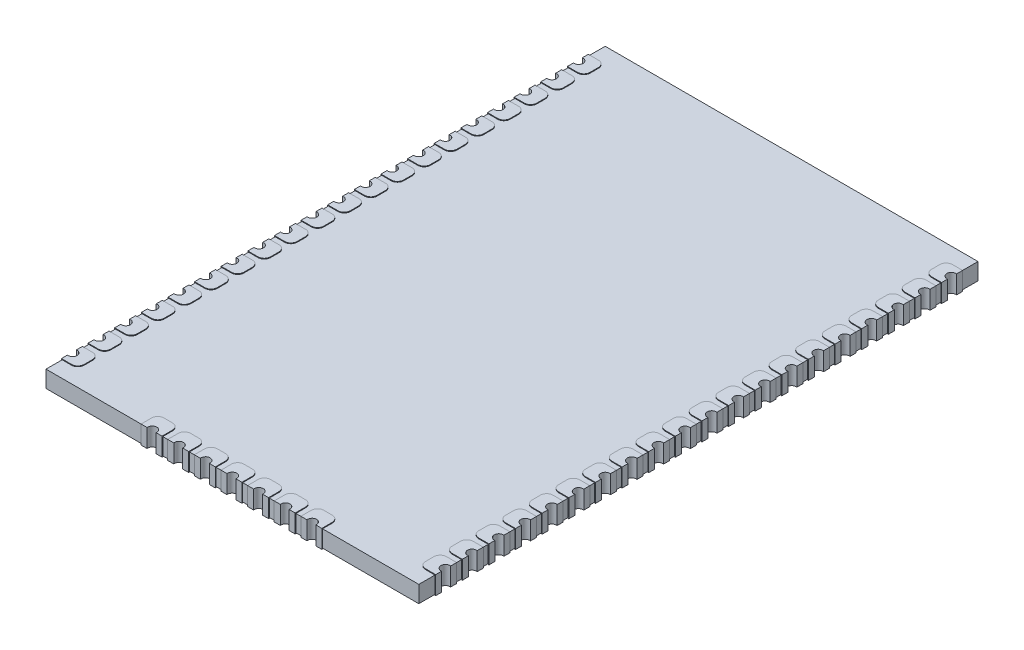
SolidWorks part; units mm, degrees
ref_plane "Front Plane" through (0, 0, 0) normal (0, 0, 1) x (1, 0, 0)
ref_plane "Top Plane" through (0, 0, 0) normal (0, 1, 0) x (1, 0, 0)
ref_plane "Right Plane" through (0, 0, 0) normal (1, 0, 0) x (0, 0, -1)
sketch "Sketch1" plane through (0, 0, 0) normal (0, 1, 0) x (1, 0, 0)
  line L1 (-8.89, 13.335) -> (8.89, 13.335)
  line L2 (-8.89, 13.335) -> (-8.89, -13.335)
  line L3 (-8.89, -13.335) -> (8.89, -13.335)
  line L4 (8.89, 13.335) -> (8.89, -13.335)
  line L5 (-8.89, 13.335) -> (8.89, -13.335) construction
  line L6 (-8.89, -13.335) -> (8.89, 13.335) construction
  point P0 (0, 0)
  dimension "D1" = 26.67
  dimension "D2" = 17.78
extrude "Boss-Extrude1" add sketch "Sketch1" along normal blind 0.8
sketch "Sketch2" plane through (0, 0, 0) normal (0, -1, 0) x (1, 0, 0)
  line L0 (-8.89, -13.335) -> (-8.89, 13.335) construction
  line L1 (-8.89, 13.335) -> (8.89, 13.335) construction
  line L2 (8.89, 13.335) -> (8.89, -13.335) construction
  line L3 (8.89, -13.335) -> (-8.89, -13.335) construction
  circle A0 centre (-8.89, -12.065) radius 0.25
  circle A1 centre (-8.89, -10.795) radius 0.25
  circle A2 centre (-8.89, -9.525) radius 0.25
  circle A3 centre (-8.89, -8.255) radius 0.25
  circle A4 centre (-8.89, -6.985) radius 0.25
  circle A5 centre (-8.89, -5.715) radius 0.25
  circle A6 centre (-8.89, -4.445) radius 0.25
  circle A7 centre (-8.89, -3.175) radius 0.25
  circle A8 centre (-8.89, -1.905) radius 0.25
  circle A9 centre (-8.89, -0.635) radius 0.25
  circle A10 centre (-8.89, 0.635) radius 0.25
  circle A11 centre (-8.89, 1.905) radius 0.25
  circle A12 centre (-8.89, 3.175) radius 0.25
  circle A13 centre (-8.89, 4.445) radius 0.25
  circle A14 centre (-8.89, 5.715) radius 0.25
  circle A15 centre (-8.89, 6.985) radius 0.25
  circle A16 centre (-8.89, 8.255) radius 0.25
  circle A17 centre (-8.89, 9.525) radius 0.25
  circle A18 centre (-8.89, 10.795) radius 0.25
  circle A19 centre (-8.89, 12.065) radius 0.25
  circle A20 centre (8.89, -10.795) radius 0.25
  circle A21 centre (8.89, -9.525) radius 0.25
  circle A22 centre (8.89, -8.255) radius 0.25
  circle A23 centre (8.89, -6.985) radius 0.25
  circle A24 centre (8.89, -5.715) radius 0.25
  circle A25 centre (8.89, -4.445) radius 0.25
  circle A26 centre (8.89, -3.175) radius 0.25
  circle A27 centre (8.89, -1.905) radius 0.25
  circle A28 centre (8.89, -0.635) radius 0.25
  circle A29 centre (8.89, 0.635) radius 0.25
  circle A30 centre (8.89, 1.905) radius 0.25
  circle A31 centre (8.89, 3.175) radius 0.25
  circle A32 centre (8.89, 4.445) radius 0.25
  circle A33 centre (8.89, 5.715) radius 0.25
  circle A34 centre (8.89, 6.985) radius 0.25
  circle A35 centre (8.89, 8.255) radius 0.25
  circle A36 centre (8.89, 9.525) radius 0.25
  circle A37 centre (8.89, 10.795) radius 0.25
  circle A38 centre (8.89, 12.065) radius 0.25
  circle A39 centre (8.89, -12.065) radius 0.25
  circle A40 centre (-3.81, 13.335) radius 0.25
  circle A41 centre (-2.54, 13.335) radius 0.25
  circle A42 centre (-1.27, 13.335) radius 0.25
  circle A43 centre (0, 13.335) radius 0.25
  circle A44 centre (1.27, 13.335) radius 0.25
  circle A45 centre (2.54, 13.335) radius 0.25
  circle A46 centre (3.81, 13.335) radius 0.25
  dimension "D1" = 0.5
  dimension "D6" = 5.08
  dimension "D7" = 1.27
  dimension "D11" = 17.78
  dimension "D4" = 5.08
  dimension "D8" = 1.27
  dimension "D9" = 26.67
  dimension "D10" = 25.4
  dimension "D3" = 20
  dimension "D2" = 2
  dimension "D5" = 7
extrude "Cut-Extrude1" cut sketch "Sketch2" against normal blind 1
sketch "Sketch3" plane through (0, 0, 0) normal (0, -1, 0) x (1, 0, 0)
  line L0 (-8.89, 12.065) -> (-8.13, 12.065) construction
  line L1 (-8.89, 11.565) -> (-8.44, 11.565)
  line L2 (-8.89, 12.565) -> (-8.44, 12.565)
  line L3 (-8.89, 11.565) -> (-8.13, 11.565) construction
  line L4 (-8.89, 12.565) -> (-8.13, 12.565) construction
  line L5 (-8.89, 10.295) -> (-8.44, 10.295)
  line L6 (-8.89, 12.565) -> (-8.925, 12.565)
  line L7 (-8.89, 11.565) -> (-8.925, 11.565)
  line L8 (-8.925, 11.045) -> (-8.925, 11.8529)
  line L9 (-8.925, 12.2771) -> (-8.925, 13.335)
  line L10 (-8.925, 11.565) -> (-8.925, 11.8529)
  line L11 (-8.925, 12.2771) -> (-8.925, 12.565)
  line L12 (-8.14, 12.265) -> (-8.14, 11.865)
  line L13 (-8.89, 11.295) -> (-8.44, 11.295)
  line L14 (-8.89, 11.295) -> (-8.925, 11.295)
  line L15 (-8.89, 10.295) -> (-8.925, 10.295)
  line L16 (-8.925, 10.295) -> (-8.925, 10.5829)
  line L17 (-8.925, 11.0071) -> (-8.925, 11.295)
  line L18 (-8.14, 10.995) -> (-8.14, 10.595)
  line L19 (-8.89, 10.795) -> (-8.13, 10.795) construction
  line L20 (-8.89, 9.025) -> (-8.44, 9.025)
  line L21 (-8.89, 10.025) -> (-8.44, 10.025)
  line L22 (-8.89, 10.025) -> (-8.925, 10.025)
  line L23 (-8.89, 9.025) -> (-8.925, 9.025)
  line L24 (-8.925, 9.025) -> (-8.925, 9.3129)
  line L25 (-8.925, 9.7371) -> (-8.925, 10.025)
  line L26 (-8.14, 9.725) -> (-8.14, 9.325)
  line L27 (-8.89, 9.525) -> (-8.13, 9.525) construction
  line L28 (-8.89, 7.755) -> (-8.44, 7.755)
  line L29 (-8.89, 8.755) -> (-8.44, 8.755)
  line L30 (-8.89, 8.755) -> (-8.925, 8.755)
  line L31 (-8.89, 7.755) -> (-8.925, 7.755)
  line L32 (-8.925, 7.755) -> (-8.925, 8.0429)
  line L33 (-8.925, 8.4671) -> (-8.925, 8.755)
  line L34 (-8.14, 8.455) -> (-8.14, 8.055)
  line L35 (-8.89, 8.255) -> (-8.13, 8.255) construction
  line L36 (-8.89, 6.485) -> (-8.44, 6.485)
  line L37 (-8.89, 7.485) -> (-8.44, 7.485)
  line L38 (-8.89, 7.485) -> (-8.925, 7.485)
  line L39 (-8.89, 6.485) -> (-8.925, 6.485)
  line L40 (-8.925, 6.485) -> (-8.925, 6.7729)
  line L41 (-8.925, 7.1971) -> (-8.925, 7.485)
  line L42 (-8.14, 7.185) -> (-8.14, 6.785)
  line L43 (-8.89, 6.985) -> (-8.13, 6.985) construction
  line L44 (-8.89, 5.215) -> (-8.44, 5.215)
  line L45 (-8.89, 6.215) -> (-8.44, 6.215)
  line L46 (-8.89, 6.215) -> (-8.925, 6.215)
  line L47 (-8.89, 5.215) -> (-8.925, 5.215)
  line L48 (-8.925, 5.215) -> (-8.925, 5.5029)
  line L49 (-8.925, 5.9271) -> (-8.925, 6.215)
  line L50 (-8.14, 5.915) -> (-8.14, 5.515)
  line L51 (-8.89, 5.715) -> (-8.13, 5.715) construction
  line L52 (-8.89, 3.945) -> (-8.44, 3.945)
  line L53 (-8.89, 4.945) -> (-8.44, 4.945)
  line L54 (-8.89, 4.945) -> (-8.925, 4.945)
  line L55 (-8.89, 3.945) -> (-8.925, 3.945)
  line L56 (-8.925, 3.945) -> (-8.925, 4.2329)
  line L57 (-8.925, 4.6571) -> (-8.925, 4.945)
  line L58 (-8.14, 4.645) -> (-8.14, 4.245)
  line L59 (-8.89, 4.445) -> (-8.13, 4.445) construction
  line L60 (-8.89, 2.675) -> (-8.44, 2.675)
  line L61 (-8.89, 3.675) -> (-8.44, 3.675)
  line L62 (-8.89, 3.675) -> (-8.925, 3.675)
  line L63 (-8.89, 2.675) -> (-8.925, 2.675)
  line L64 (-8.925, 2.675) -> (-8.925, 2.9629)
  line L65 (-8.925, 3.3871) -> (-8.925, 3.675)
  line L66 (-8.14, 3.375) -> (-8.14, 2.975)
  line L67 (-8.89, 3.175) -> (-8.13, 3.175) construction
  line L68 (-8.89, 1.405) -> (-8.44, 1.405)
  line L69 (-8.89, 2.405) -> (-8.44, 2.405)
  line L70 (-8.89, 2.405) -> (-8.925, 2.405)
  line L71 (-8.89, 1.405) -> (-8.925, 1.405)
  line L72 (-8.925, 1.405) -> (-8.925, 1.6929)
  line L73 (-8.925, 2.1171) -> (-8.925, 2.405)
  line L74 (-8.14, 2.105) -> (-8.14, 1.705)
  line L75 (-8.89, 1.905) -> (-8.13, 1.905) construction
  line L76 (-8.89, 0.135) -> (-8.44, 0.135)
  line L77 (-8.89, 1.135) -> (-8.44, 1.135)
  line L78 (-8.89, 1.135) -> (-8.925, 1.135)
  line L79 (-8.89, 0.135) -> (-8.925, 0.135)
  line L80 (-8.925, 0.135) -> (-8.925, 0.4229)
  line L81 (-8.925, 0.8471) -> (-8.925, 1.135)
  line L82 (-8.14, 0.835) -> (-8.14, 0.435)
  line L83 (-8.89, 0.635) -> (-8.13, 0.635) construction
  line L84 (-8.89, -1.135) -> (-8.44, -1.135)
  line L85 (-8.89, -0.135) -> (-8.44, -0.135)
  line L86 (-8.89, -0.135) -> (-8.925, -0.135)
  line L87 (-8.89, -1.135) -> (-8.925, -1.135)
  line L88 (-8.925, -1.135) -> (-8.925, -0.8471)
  line L89 (-8.925, -0.4229) -> (-8.925, -0.135)
  line L90 (-8.14, -0.435) -> (-8.14, -0.835)
  line L91 (-8.89, -0.635) -> (-8.13, -0.635) construction
  line L92 (-8.89, -2.405) -> (-8.44, -2.405)
  line L93 (-8.89, -1.405) -> (-8.44, -1.405)
  line L94 (-8.89, -1.405) -> (-8.925, -1.405)
  line L95 (-8.89, -2.405) -> (-8.925, -2.405)
  line L96 (-8.925, -2.405) -> (-8.925, -2.1171)
  line L97 (-8.925, -1.6929) -> (-8.925, -1.405)
  line L98 (-8.14, -1.705) -> (-8.14, -2.105)
  line L99 (-8.89, -1.905) -> (-8.13, -1.905) construction
  line L100 (-8.89, -3.675) -> (-8.44, -3.675)
  line L101 (-8.89, -2.675) -> (-8.44, -2.675)
  line L102 (-8.89, -2.675) -> (-8.925, -2.675)
  line L103 (-8.89, -3.675) -> (-8.925, -3.675)
  line L104 (-8.925, -3.675) -> (-8.925, -3.3871)
  line L105 (-8.925, -2.9629) -> (-8.925, -2.675)
  line L106 (-8.14, -2.975) -> (-8.14, -3.375)
  line L107 (-8.89, -3.175) -> (-8.13, -3.175) construction
  line L108 (-8.89, -4.945) -> (-8.44, -4.945)
  line L109 (-8.89, -3.945) -> (-8.44, -3.945)
  line L110 (-8.89, -3.945) -> (-8.925, -3.945)
  line L111 (-8.89, -4.945) -> (-8.925, -4.945)
  line L112 (-8.925, -4.945) -> (-8.925, -4.6571)
  line L113 (-8.925, -4.2329) -> (-8.925, -3.945)
  line L114 (-8.14, -4.245) -> (-8.14, -4.645)
  line L115 (-8.89, -4.445) -> (-8.13, -4.445) construction
  line L116 (-8.89, -6.215) -> (-8.44, -6.215)
  line L117 (-8.89, -5.215) -> (-8.44, -5.215)
  line L118 (-8.89, -5.215) -> (-8.925, -5.215)
  line L119 (-8.89, -6.215) -> (-8.925, -6.215)
  line L120 (-8.925, -6.215) -> (-8.925, -5.9271)
  line L121 (-8.925, -5.5029) -> (-8.925, -5.215)
  line L122 (-8.14, -5.515) -> (-8.14, -5.915)
  line L123 (-8.89, -5.715) -> (-8.13, -5.715) construction
  line L124 (-8.89, -7.485) -> (-8.44, -7.485)
  line L125 (-8.89, -6.485) -> (-8.44, -6.485)
  line L126 (-8.89, -6.485) -> (-8.925, -6.485)
  line L127 (-8.89, -7.485) -> (-8.925, -7.485)
  line L128 (-8.925, -7.485) -> (-8.925, -7.1971)
  line L129 (-8.925, -6.7729) -> (-8.925, -6.485)
  line L130 (-8.14, -6.785) -> (-8.14, -7.185)
  line L131 (-8.89, -6.985) -> (-8.13, -6.985) construction
  line L132 (-8.89, -8.755) -> (-8.44, -8.755)
  line L133 (-8.89, -7.755) -> (-8.44, -7.755)
  line L134 (-8.89, -7.755) -> (-8.925, -7.755)
  line L135 (-8.89, -8.755) -> (-8.925, -8.755)
  line L136 (-8.925, -8.755) -> (-8.925, -8.4671)
  line L137 (-8.925, -8.0429) -> (-8.925, -7.755)
  line L138 (-8.14, -8.055) -> (-8.14, -8.455)
  line L139 (-8.89, -8.255) -> (-8.13, -8.255) construction
  line L140 (-8.89, -10.025) -> (-8.44, -10.025)
  line L141 (-8.89, -9.025) -> (-8.44, -9.025)
  line L142 (-8.89, -9.025) -> (-8.925, -9.025)
  line L143 (-8.89, -10.025) -> (-8.925, -10.025)
  line L144 (-8.925, -10.025) -> (-8.925, -9.7371)
  line L145 (-8.925, -9.3129) -> (-8.925, -9.025)
  line L146 (-8.14, -9.325) -> (-8.14, -9.725)
  line L147 (-8.89, -9.525) -> (-8.13, -9.525) construction
  line L148 (-8.89, -11.295) -> (-8.44, -11.295)
  line L149 (-8.89, -10.295) -> (-8.44, -10.295)
  line L150 (-8.89, -10.295) -> (-8.925, -10.295)
  line L151 (-8.89, -11.295) -> (-8.925, -11.295)
  line L152 (-8.925, -11.295) -> (-8.925, -11.0071)
  line L153 (-8.925, -10.5829) -> (-8.925, -10.295)
  line L154 (-8.14, -10.595) -> (-8.14, -10.995)
  line L155 (-8.89, -10.795) -> (-8.13, -10.795) construction
  line L156 (-8.89, -12.565) -> (-8.44, -12.565)
  line L157 (-8.89, -11.565) -> (-8.44, -11.565)
  line L158 (-8.89, -11.565) -> (-8.925, -11.565)
  line L159 (-8.89, -12.565) -> (-8.925, -12.565)
  line L160 (-8.925, -12.565) -> (-8.925, -12.2771)
  line L161 (-8.925, -11.8529) -> (-8.925, -11.565)
  line L162 (-8.14, -11.865) -> (-8.14, -12.265)
  line L163 (-8.89, -12.065) -> (-8.13, -12.065) construction
  line L164 (0, 0) -> (0, 0.426) construction
  line L165 (0, 0) -> (0, 8.246) construction
  line L166 (8.89, -12.065) -> (8.13, -12.065) construction
  line L167 (8.89, -10.795) -> (8.13, -10.795) construction
  line L168 (8.89, -9.525) -> (8.13, -9.525) construction
  line L169 (8.89, -8.255) -> (8.13, -8.255) construction
  line L170 (8.89, -6.985) -> (8.13, -6.985) construction
  line L171 (8.89, -5.715) -> (8.13, -5.715) construction
  line L172 (8.89, -4.445) -> (8.13, -4.445) construction
  line L173 (8.89, -3.175) -> (8.13, -3.175) construction
  line L174 (8.89, -1.905) -> (8.13, -1.905) construction
  line L175 (8.89, -0.635) -> (8.13, -0.635) construction
  line L176 (8.89, 0.635) -> (8.13, 0.635) construction
  line L177 (8.89, 1.905) -> (8.13, 1.905) construction
  line L178 (8.89, 3.175) -> (8.13, 3.175) construction
  line L179 (8.89, 4.445) -> (8.13, 4.445) construction
  line L180 (8.89, 5.715) -> (8.13, 5.715) construction
  line L181 (8.89, 6.985) -> (8.13, 6.985) construction
  line L182 (8.89, 8.255) -> (8.13, 8.255) construction
  line L183 (8.89, 9.525) -> (8.13, 9.525) construction
  line L184 (8.89, 10.795) -> (8.13, 10.795) construction
  line L185 (8.89, 12.065) -> (8.13, 12.065) construction
  line L186 (8.14, -11.865) -> (8.14, -12.265)
  line L187 (8.925, -11.8529) -> (8.925, -11.565)
  line L188 (8.925, -12.565) -> (8.925, -12.2771)
  line L189 (8.89, -12.565) -> (8.925, -12.565)
  line L190 (8.89, -11.565) -> (8.925, -11.565)
  line L191 (8.89, -11.565) -> (8.44, -11.565)
  line L192 (8.89, -12.565) -> (8.44, -12.565)
  line L193 (8.14, -10.595) -> (8.14, -10.995)
  line L194 (8.925, -10.5829) -> (8.925, -10.295)
  line L195 (8.925, -11.295) -> (8.925, -11.0071)
  line L196 (8.89, -11.295) -> (8.925, -11.295)
  line L197 (8.89, -10.295) -> (8.925, -10.295)
  line L198 (8.89, -10.295) -> (8.44, -10.295)
  line L199 (8.89, -11.295) -> (8.44, -11.295)
  line L200 (8.14, -9.325) -> (8.14, -9.725)
  line L201 (8.925, -9.3129) -> (8.925, -9.025)
  line L202 (8.925, -10.025) -> (8.925, -9.7371)
  line L203 (8.89, -10.025) -> (8.925, -10.025)
  line L204 (8.89, -9.025) -> (8.925, -9.025)
  line L205 (8.89, -9.025) -> (8.44, -9.025)
  line L206 (8.89, -10.025) -> (8.44, -10.025)
  line L207 (8.14, -8.055) -> (8.14, -8.455)
  line L208 (8.925, -8.0429) -> (8.925, -7.755)
  line L209 (8.925, -8.755) -> (8.925, -8.4671)
  line L210 (8.89, -8.755) -> (8.925, -8.755)
  line L211 (8.89, -7.755) -> (8.925, -7.755)
  line L212 (8.89, -7.755) -> (8.44, -7.755)
  line L213 (8.89, -8.755) -> (8.44, -8.755)
  line L214 (8.14, -6.785) -> (8.14, -7.185)
  line L215 (8.925, -6.7729) -> (8.925, -6.485)
  line L216 (8.925, -7.485) -> (8.925, -7.1971)
  line L217 (8.89, -7.485) -> (8.925, -7.485)
  line L218 (8.89, -6.485) -> (8.925, -6.485)
  line L219 (8.89, -6.485) -> (8.44, -6.485)
  line L220 (8.89, -7.485) -> (8.44, -7.485)
  line L221 (8.14, -5.515) -> (8.14, -5.915)
  line L222 (8.925, -5.5029) -> (8.925, -5.215)
  line L223 (8.925, -6.215) -> (8.925, -5.9271)
  line L224 (8.89, -6.215) -> (8.925, -6.215)
  line L225 (8.89, -5.215) -> (8.925, -5.215)
  line L226 (8.89, -5.215) -> (8.44, -5.215)
  line L227 (8.89, -6.215) -> (8.44, -6.215)
  line L228 (8.14, -4.245) -> (8.14, -4.645)
  line L229 (8.925, -4.2329) -> (8.925, -3.945)
  line L230 (8.925, -4.945) -> (8.925, -4.6571)
  line L231 (8.89, -4.945) -> (8.925, -4.945)
  line L232 (8.89, -3.945) -> (8.925, -3.945)
  line L233 (8.89, -3.945) -> (8.44, -3.945)
  line L234 (8.89, -4.945) -> (8.44, -4.945)
  line L235 (8.14, -2.975) -> (8.14, -3.375)
  line L236 (8.925, -2.9629) -> (8.925, -2.675)
  line L237 (8.925, -3.675) -> (8.925, -3.3871)
  line L238 (8.89, -3.675) -> (8.925, -3.675)
  line L239 (8.89, -2.675) -> (8.925, -2.675)
  line L240 (8.89, -2.675) -> (8.44, -2.675)
  line L241 (8.89, -3.675) -> (8.44, -3.675)
  line L242 (8.14, -1.705) -> (8.14, -2.105)
  line L243 (8.925, -1.6929) -> (8.925, -1.405)
  line L244 (8.925, -2.405) -> (8.925, -2.1171)
  line L245 (8.89, -2.405) -> (8.925, -2.405)
  line L246 (8.89, -1.405) -> (8.925, -1.405)
  line L247 (8.89, -1.405) -> (8.44, -1.405)
  line L248 (8.89, -2.405) -> (8.44, -2.405)
  line L249 (8.14, -0.435) -> (8.14, -0.835)
  line L250 (8.925, -0.4229) -> (8.925, -0.135)
  line L251 (8.925, -1.135) -> (8.925, -0.8471)
  line L252 (8.89, -1.135) -> (8.925, -1.135)
  line L253 (8.89, -0.135) -> (8.925, -0.135)
  line L254 (8.89, -0.135) -> (8.44, -0.135)
  line L255 (8.89, -1.135) -> (8.44, -1.135)
  line L256 (8.14, 0.835) -> (8.14, 0.435)
  line L257 (8.925, 0.8471) -> (8.925, 1.135)
  line L258 (8.925, 0.135) -> (8.925, 0.4229)
  line L259 (8.89, 0.135) -> (8.925, 0.135)
  line L260 (8.89, 1.135) -> (8.925, 1.135)
  line L261 (8.89, 1.135) -> (8.44, 1.135)
  line L262 (8.89, 0.135) -> (8.44, 0.135)
  line L263 (8.14, 2.105) -> (8.14, 1.705)
  line L264 (8.925, 2.1171) -> (8.925, 2.405)
  line L265 (8.925, 1.405) -> (8.925, 1.6929)
  line L266 (8.89, 1.405) -> (8.925, 1.405)
  line L267 (8.89, 2.405) -> (8.925, 2.405)
  line L268 (8.89, 2.405) -> (8.44, 2.405)
  line L269 (8.89, 1.405) -> (8.44, 1.405)
  line L270 (8.14, 3.375) -> (8.14, 2.975)
  line L271 (8.925, 3.3871) -> (8.925, 3.675)
  line L272 (8.925, 2.675) -> (8.925, 2.9629)
  line L273 (8.89, 2.675) -> (8.925, 2.675)
  line L274 (8.89, 3.675) -> (8.925, 3.675)
  line L275 (8.89, 3.675) -> (8.44, 3.675)
  line L276 (8.89, 2.675) -> (8.44, 2.675)
  line L277 (8.14, 4.645) -> (8.14, 4.245)
  line L278 (8.925, 4.6571) -> (8.925, 4.945)
  line L279 (8.925, 3.945) -> (8.925, 4.2329)
  line L280 (8.89, 3.945) -> (8.925, 3.945)
  line L281 (8.89, 4.945) -> (8.925, 4.945)
  line L282 (8.89, 4.945) -> (8.44, 4.945)
  line L283 (8.89, 3.945) -> (8.44, 3.945)
  line L284 (8.14, 5.915) -> (8.14, 5.515)
  line L285 (8.925, 5.9271) -> (8.925, 6.215)
  line L286 (8.925, 5.215) -> (8.925, 5.5029)
  line L287 (8.89, 5.215) -> (8.925, 5.215)
  line L288 (8.89, 6.215) -> (8.925, 6.215)
  line L289 (8.89, 6.215) -> (8.44, 6.215)
  line L290 (8.89, 5.215) -> (8.44, 5.215)
  line L291 (8.14, 7.185) -> (8.14, 6.785)
  line L292 (8.925, 7.1971) -> (8.925, 7.485)
  line L293 (8.925, 6.485) -> (8.925, 6.7729)
  line L294 (8.89, 6.485) -> (8.925, 6.485)
  line L295 (8.89, 7.485) -> (8.925, 7.485)
  line L296 (8.89, 7.485) -> (8.44, 7.485)
  line L297 (8.89, 6.485) -> (8.44, 6.485)
  line L298 (8.14, 8.455) -> (8.14, 8.055)
  line L299 (8.925, 8.4671) -> (8.925, 8.755)
  line L300 (8.925, 7.755) -> (8.925, 8.0429)
  line L301 (8.89, 7.755) -> (8.925, 7.755)
  line L302 (8.89, 8.755) -> (8.925, 8.755)
  line L303 (8.89, 8.755) -> (8.44, 8.755)
  line L304 (8.89, 7.755) -> (8.44, 7.755)
  line L305 (8.14, 9.725) -> (8.14, 9.325)
  line L306 (8.925, 9.7371) -> (8.925, 10.025)
  line L307 (8.925, 9.025) -> (8.925, 9.3129)
  line L308 (8.89, 9.025) -> (8.925, 9.025)
  line L309 (8.89, 10.025) -> (8.925, 10.025)
  line L310 (8.89, 10.025) -> (8.44, 10.025)
  line L311 (8.89, 9.025) -> (8.44, 9.025)
  line L312 (8.14, 10.995) -> (8.14, 10.595)
  line L313 (8.925, 11.0071) -> (8.925, 11.295)
  line L314 (8.925, 10.295) -> (8.925, 10.5829)
  line L315 (8.89, 10.295) -> (8.925, 10.295)
  line L316 (8.89, 11.295) -> (8.925, 11.295)
  line L317 (8.89, 11.295) -> (8.44, 11.295)
  line L318 (8.14, 12.265) -> (8.14, 11.865)
  line L319 (8.925, 12.2771) -> (8.925, 12.565)
  line L320 (8.925, 11.565) -> (8.925, 11.8529)
  line L321 (8.89, 11.565) -> (8.925, 11.565)
  line L322 (8.89, 12.565) -> (8.925, 12.565)
  line L323 (8.89, 10.295) -> (8.44, 10.295)
  line L324 (8.89, 12.565) -> (8.44, 12.565)
  line L325 (8.89, 11.565) -> (8.44, 11.565)
  line L326 (-3.6079, 13.37) -> (-3.32, 13.37)
  line L327 (-3.32, 13.335) -> (-3.32, 13.37)
  line L328 (-3.62, 12.575) -> (-4.02, 12.575)
  line L329 (-4.32, 13.335) -> (-4.32, 13.37)
  line L330 (-3.82, 13.335) -> (-3.82, 12.575) construction
  line L331 (-4.32, 13.335) -> (-4.32, 12.875)
  line L332 (-4.32, 13.37) -> (-4.0321, 13.37)
  line L333 (-3.32, 13.335) -> (-3.32, 12.875)
  line L334 (-2.3379, 13.37) -> (-2.05, 13.37)
  line L335 (-2.05, 13.335) -> (-2.05, 13.37)
  line L336 (-2.35, 12.575) -> (-2.75, 12.575)
  line L337 (-3.05, 13.335) -> (-3.05, 13.37)
  line L338 (-3.05, 13.335) -> (-3.05, 12.875)
  line L339 (-3.05, 13.37) -> (-2.7621, 13.37)
  line L340 (-2.05, 13.335) -> (-2.05, 12.875)
  line L341 (-2.55, 13.335) -> (-2.55, 12.575) construction
  line L342 (-1.0679, 13.37) -> (-0.78, 13.37)
  line L343 (-0.78, 13.335) -> (-0.78, 13.37)
  line L344 (-1.08, 12.575) -> (-1.48, 12.575)
  line L345 (-1.78, 13.335) -> (-1.78, 13.37)
  line L346 (-1.78, 13.335) -> (-1.78, 12.875)
  line L347 (-1.78, 13.37) -> (-1.4921, 13.37)
  line L348 (-0.78, 13.335) -> (-0.78, 12.875)
  line L349 (-1.28, 13.335) -> (-1.28, 12.575) construction
  line L350 (0.2021, 13.37) -> (0.49, 13.37)
  line L351 (0.49, 13.335) -> (0.49, 13.37)
  line L352 (0.19, 12.575) -> (-0.21, 12.575)
  line L353 (-0.51, 13.335) -> (-0.51, 13.37)
  line L354 (-0.51, 13.335) -> (-0.51, 12.875)
  line L355 (-0.51, 13.37) -> (-0.2221, 13.37)
  line L356 (0.49, 13.335) -> (0.49, 12.875)
  line L357 (-0.01, 13.335) -> (-0.01, 12.575) construction
  line L358 (1.4721, 13.37) -> (1.76, 13.37)
  line L359 (1.76, 13.335) -> (1.76, 13.37)
  line L360 (1.46, 12.575) -> (1.06, 12.575)
  line L361 (0.76, 13.335) -> (0.76, 13.37)
  line L362 (0.76, 13.335) -> (0.76, 12.875)
  line L363 (0.76, 13.37) -> (1.0479, 13.37)
  line L364 (1.76, 13.335) -> (1.76, 12.875)
  line L365 (1.26, 13.335) -> (1.26, 12.575) construction
  line L366 (2.7421, 13.37) -> (3.03, 13.37)
  line L367 (3.03, 13.335) -> (3.03, 13.37)
  line L368 (2.73, 12.575) -> (2.33, 12.575)
  line L369 (2.03, 13.335) -> (2.03, 13.37)
  line L370 (2.03, 13.335) -> (2.03, 12.875)
  line L371 (2.03, 13.37) -> (2.3179, 13.37)
  line L372 (3.03, 13.335) -> (3.03, 12.875)
  line L373 (2.53, 13.335) -> (2.53, 12.575) construction
  line L374 (4.0121, 13.37) -> (4.3, 13.37)
  line L375 (4.3, 13.335) -> (4.3, 13.37)
  line L376 (4, 12.575) -> (3.6, 12.575)
  line L377 (3.3, 13.335) -> (3.3, 13.37)
  line L378 (3.3, 13.335) -> (3.3, 12.875)
  line L379 (3.3, 13.37) -> (3.5879, 13.37)
  line L380 (4.3, 13.335) -> (4.3, 12.875)
  line L381 (3.8, 13.335) -> (3.8, 12.575) construction
  arc A0 (-8.44, 11.565) -> (-8.14, 11.865) centre (-8.44, 11.865) ccw
  arc A1 (-8.44, 12.565) -> (-8.14, 12.265) centre (-8.44, 12.265) cw
  arc A2 (-8.44, 10.295) -> (-8.14, 10.595) centre (-8.44, 10.595) ccw
  arc A3 (-8.44, 11.295) -> (-8.14, 10.995) centre (-8.44, 10.995) cw
  arc A4 (-8.925, 11.8529) -> (-8.925, 12.2771) centre (-8.89, 12.065) ccw
  arc A5 (-8.925, 11.8529) -> (-8.925, 12.2771) centre (-8.89, 12.065) ccw
  arc A6 (-8.925, 10.5829) -> (-8.925, 11.0071) centre (-8.89, 10.795) ccw
  arc A7 (-8.44, 9.025) -> (-8.14, 9.325) centre (-8.44, 9.325) ccw
  arc A8 (-8.44, 10.025) -> (-8.14, 9.725) centre (-8.44, 9.725) cw
  arc A9 (-8.925, 9.3129) -> (-8.925, 9.7371) centre (-8.89, 9.525) ccw
  arc A10 (-8.44, 7.755) -> (-8.14, 8.055) centre (-8.44, 8.055) ccw
  arc A11 (-8.44, 8.755) -> (-8.14, 8.455) centre (-8.44, 8.455) cw
  arc A12 (-8.925, 8.0429) -> (-8.925, 8.4671) centre (-8.89, 8.255) ccw
  arc A13 (-8.44, 6.485) -> (-8.14, 6.785) centre (-8.44, 6.785) ccw
  arc A14 (-8.44, 7.485) -> (-8.14, 7.185) centre (-8.44, 7.185) cw
  arc A15 (-8.925, 6.7729) -> (-8.925, 7.1971) centre (-8.89, 6.985) ccw
  arc A16 (-8.44, 5.215) -> (-8.14, 5.515) centre (-8.44, 5.515) ccw
  arc A17 (-8.44, 6.215) -> (-8.14, 5.915) centre (-8.44, 5.915) cw
  arc A18 (-8.925, 5.5029) -> (-8.925, 5.9271) centre (-8.89, 5.715) ccw
  arc A19 (-8.44, 3.945) -> (-8.14, 4.245) centre (-8.44, 4.245) ccw
  arc A20 (-8.44, 4.945) -> (-8.14, 4.645) centre (-8.44, 4.645) cw
  arc A21 (-8.925, 4.2329) -> (-8.925, 4.6571) centre (-8.89, 4.445) ccw
  arc A22 (-8.44, 2.675) -> (-8.14, 2.975) centre (-8.44, 2.975) ccw
  arc A23 (-8.44, 3.675) -> (-8.14, 3.375) centre (-8.44, 3.375) cw
  arc A24 (-8.925, 2.9629) -> (-8.925, 3.3871) centre (-8.89, 3.175) ccw
  arc A25 (-8.44, 1.405) -> (-8.14, 1.705) centre (-8.44, 1.705) ccw
  arc A26 (-8.44, 2.405) -> (-8.14, 2.105) centre (-8.44, 2.105) cw
  arc A27 (-8.925, 1.6929) -> (-8.925, 2.1171) centre (-8.89, 1.905) ccw
  arc A28 (-8.44, 0.135) -> (-8.14, 0.435) centre (-8.44, 0.435) ccw
  arc A29 (-8.44, 1.135) -> (-8.14, 0.835) centre (-8.44, 0.835) cw
  arc A30 (-8.925, 0.4229) -> (-8.925, 0.8471) centre (-8.89, 0.635) ccw
  arc A31 (-8.44, -1.135) -> (-8.14, -0.835) centre (-8.44, -0.835) ccw
  arc A32 (-8.44, -0.135) -> (-8.14, -0.435) centre (-8.44, -0.435) cw
  arc A33 (-8.925, -0.8471) -> (-8.925, -0.4229) centre (-8.89, -0.635) ccw
  arc A34 (-8.44, -2.405) -> (-8.14, -2.105) centre (-8.44, -2.105) ccw
  arc A35 (-8.44, -1.405) -> (-8.14, -1.705) centre (-8.44, -1.705) cw
  arc A36 (-8.925, -2.1171) -> (-8.925, -1.6929) centre (-8.89, -1.905) ccw
  arc A37 (-8.44, -3.675) -> (-8.14, -3.375) centre (-8.44, -3.375) ccw
  arc A38 (-8.44, -2.675) -> (-8.14, -2.975) centre (-8.44, -2.975) cw
  arc A39 (-8.925, -3.3871) -> (-8.925, -2.9629) centre (-8.89, -3.175) ccw
  arc A40 (-8.44, -4.945) -> (-8.14, -4.645) centre (-8.44, -4.645) ccw
  arc A41 (-8.44, -3.945) -> (-8.14, -4.245) centre (-8.44, -4.245) cw
  arc A42 (-8.925, -4.6571) -> (-8.925, -4.2329) centre (-8.89, -4.445) ccw
  arc A43 (-8.44, -6.215) -> (-8.14, -5.915) centre (-8.44, -5.915) ccw
  arc A44 (-8.44, -5.215) -> (-8.14, -5.515) centre (-8.44, -5.515) cw
  arc A45 (-8.925, -5.9271) -> (-8.925, -5.5029) centre (-8.89, -5.715) ccw
  arc A46 (-8.44, -7.485) -> (-8.14, -7.185) centre (-8.44, -7.185) ccw
  arc A47 (-8.44, -6.485) -> (-8.14, -6.785) centre (-8.44, -6.785) cw
  arc A48 (-8.925, -7.1971) -> (-8.925, -6.7729) centre (-8.89, -6.985) ccw
  arc A49 (-8.44, -8.755) -> (-8.14, -8.455) centre (-8.44, -8.455) ccw
  arc A50 (-8.44, -7.755) -> (-8.14, -8.055) centre (-8.44, -8.055) cw
  arc A51 (-8.925, -8.4671) -> (-8.925, -8.0429) centre (-8.89, -8.255) ccw
  arc A52 (-8.44, -10.025) -> (-8.14, -9.725) centre (-8.44, -9.725) ccw
  arc A53 (-8.44, -9.025) -> (-8.14, -9.325) centre (-8.44, -9.325) cw
  arc A54 (-8.925, -9.7371) -> (-8.925, -9.3129) centre (-8.89, -9.525) ccw
  arc A55 (-8.44, -11.295) -> (-8.14, -10.995) centre (-8.44, -10.995) ccw
  arc A56 (-8.44, -10.295) -> (-8.14, -10.595) centre (-8.44, -10.595) cw
  arc A57 (-8.925, -11.0071) -> (-8.925, -10.5829) centre (-8.89, -10.795) ccw
  arc A58 (-8.44, -12.565) -> (-8.14, -12.265) centre (-8.44, -12.265) ccw
  arc A59 (-8.44, -11.565) -> (-8.14, -11.865) centre (-8.44, -11.865) cw
  arc A60 (-8.925, -12.2771) -> (-8.925, -11.8529) centre (-8.89, -12.065) ccw
  arc A61 (8.925, -12.2771) -> (8.925, -11.8529) centre (8.89, -12.065) cw
  arc A62 (8.44, -11.565) -> (8.14, -11.865) centre (8.44, -11.865) ccw
  arc A63 (8.44, -12.565) -> (8.14, -12.265) centre (8.44, -12.265) cw
  arc A64 (8.925, -11.0071) -> (8.925, -10.5829) centre (8.89, -10.795) cw
  arc A65 (8.44, -10.295) -> (8.14, -10.595) centre (8.44, -10.595) ccw
  arc A66 (8.44, -11.295) -> (8.14, -10.995) centre (8.44, -10.995) cw
  arc A67 (8.925, -9.7371) -> (8.925, -9.3129) centre (8.89, -9.525) cw
  arc A68 (8.44, -9.025) -> (8.14, -9.325) centre (8.44, -9.325) ccw
  arc A69 (8.44, -10.025) -> (8.14, -9.725) centre (8.44, -9.725) cw
  arc A70 (8.925, -8.4671) -> (8.925, -8.0429) centre (8.89, -8.255) cw
  arc A71 (8.44, -7.755) -> (8.14, -8.055) centre (8.44, -8.055) ccw
  arc A72 (8.44, -8.755) -> (8.14, -8.455) centre (8.44, -8.455) cw
  arc A73 (8.925, -7.1971) -> (8.925, -6.7729) centre (8.89, -6.985) cw
  arc A74 (8.44, -6.485) -> (8.14, -6.785) centre (8.44, -6.785) ccw
  arc A75 (8.44, -7.485) -> (8.14, -7.185) centre (8.44, -7.185) cw
  arc A76 (8.925, -5.9271) -> (8.925, -5.5029) centre (8.89, -5.715) cw
  arc A77 (8.44, -5.215) -> (8.14, -5.515) centre (8.44, -5.515) ccw
  arc A78 (8.44, -6.215) -> (8.14, -5.915) centre (8.44, -5.915) cw
  arc A79 (8.925, -4.6571) -> (8.925, -4.2329) centre (8.89, -4.445) cw
  arc A80 (8.44, -3.945) -> (8.14, -4.245) centre (8.44, -4.245) ccw
  arc A81 (8.44, -4.945) -> (8.14, -4.645) centre (8.44, -4.645) cw
  arc A82 (8.925, -3.3871) -> (8.925, -2.9629) centre (8.89, -3.175) cw
  arc A83 (8.44, -2.675) -> (8.14, -2.975) centre (8.44, -2.975) ccw
  arc A84 (8.44, -3.675) -> (8.14, -3.375) centre (8.44, -3.375) cw
  arc A85 (8.925, -2.1171) -> (8.925, -1.6929) centre (8.89, -1.905) cw
  arc A86 (8.44, -1.405) -> (8.14, -1.705) centre (8.44, -1.705) ccw
  arc A87 (8.44, -2.405) -> (8.14, -2.105) centre (8.44, -2.105) cw
  arc A88 (8.925, -0.8471) -> (8.925, -0.4229) centre (8.89, -0.635) cw
  arc A89 (8.44, -0.135) -> (8.14, -0.435) centre (8.44, -0.435) ccw
  arc A90 (8.44, -1.135) -> (8.14, -0.835) centre (8.44, -0.835) cw
  arc A91 (8.925, 0.4229) -> (8.925, 0.8471) centre (8.89, 0.635) cw
  arc A92 (8.44, 1.135) -> (8.14, 0.835) centre (8.44, 0.835) ccw
  arc A93 (8.44, 0.135) -> (8.14, 0.435) centre (8.44, 0.435) cw
  arc A94 (8.925, 1.6929) -> (8.925, 2.1171) centre (8.89, 1.905) cw
  arc A95 (8.44, 2.405) -> (8.14, 2.105) centre (8.44, 2.105) ccw
  arc A96 (8.44, 1.405) -> (8.14, 1.705) centre (8.44, 1.705) cw
  arc A97 (8.925, 2.9629) -> (8.925, 3.3871) centre (8.89, 3.175) cw
  arc A98 (8.44, 3.675) -> (8.14, 3.375) centre (8.44, 3.375) ccw
  arc A99 (8.44, 2.675) -> (8.14, 2.975) centre (8.44, 2.975) cw
  arc A100 (8.925, 4.2329) -> (8.925, 4.6571) centre (8.89, 4.445) cw
  arc A101 (8.44, 4.945) -> (8.14, 4.645) centre (8.44, 4.645) ccw
  arc A102 (8.44, 3.945) -> (8.14, 4.245) centre (8.44, 4.245) cw
  arc A103 (8.925, 5.5029) -> (8.925, 5.9271) centre (8.89, 5.715) cw
  arc A104 (8.44, 6.215) -> (8.14, 5.915) centre (8.44, 5.915) ccw
  arc A105 (8.44, 5.215) -> (8.14, 5.515) centre (8.44, 5.515) cw
  arc A106 (8.925, 6.7729) -> (8.925, 7.1971) centre (8.89, 6.985) cw
  arc A107 (8.44, 7.485) -> (8.14, 7.185) centre (8.44, 7.185) ccw
  arc A108 (8.44, 6.485) -> (8.14, 6.785) centre (8.44, 6.785) cw
  arc A109 (8.925, 8.0429) -> (8.925, 8.4671) centre (8.89, 8.255) cw
  arc A110 (8.44, 8.755) -> (8.14, 8.455) centre (8.44, 8.455) ccw
  arc A111 (8.44, 7.755) -> (8.14, 8.055) centre (8.44, 8.055) cw
  arc A112 (8.925, 9.3129) -> (8.925, 9.7371) centre (8.89, 9.525) cw
  arc A113 (8.44, 10.025) -> (8.14, 9.725) centre (8.44, 9.725) ccw
  arc A114 (8.44, 9.025) -> (8.14, 9.325) centre (8.44, 9.325) cw
  arc A115 (8.925, 10.5829) -> (8.925, 11.0071) centre (8.89, 10.795) cw
  arc A116 (8.925, 11.8529) -> (8.925, 12.2771) centre (8.89, 12.065) cw
  arc A117 (8.44, 11.295) -> (8.14, 10.995) centre (8.44, 10.995) ccw
  arc A118 (8.44, 10.295) -> (8.14, 10.595) centre (8.44, 10.595) cw
  arc A119 (8.44, 12.565) -> (8.14, 12.265) centre (8.44, 12.265) ccw
  arc A120 (8.44, 11.565) -> (8.14, 11.865) centre (8.44, 11.865) cw
  arc A121 (-3.32, 12.875) -> (-3.62, 12.575) centre (-3.62, 12.875) cw
  arc A122 (-4.0321, 13.37) -> (-3.6079, 13.37) centre (-3.82, 13.335) ccw
  arc A123 (-4.32, 12.875) -> (-4.02, 12.575) centre (-4.02, 12.875) ccw
  arc A124 (-2.05, 12.875) -> (-2.35, 12.575) centre (-2.35, 12.875) cw
  arc A125 (-2.7621, 13.37) -> (-2.3379, 13.37) centre (-2.55, 13.335) ccw
  arc A126 (-3.05, 12.875) -> (-2.75, 12.575) centre (-2.75, 12.875) ccw
  arc A127 (-0.78, 12.875) -> (-1.08, 12.575) centre (-1.08, 12.875) cw
  arc A128 (-1.4921, 13.37) -> (-1.0679, 13.37) centre (-1.28, 13.335) ccw
  arc A129 (-1.78, 12.875) -> (-1.48, 12.575) centre (-1.48, 12.875) ccw
  arc A130 (0.49, 12.875) -> (0.19, 12.575) centre (0.19, 12.875) cw
  arc A131 (-0.2221, 13.37) -> (0.2021, 13.37) centre (-0.01, 13.335) ccw
  arc A132 (-0.51, 12.875) -> (-0.21, 12.575) centre (-0.21, 12.875) ccw
  arc A133 (1.76, 12.875) -> (1.46, 12.575) centre (1.46, 12.875) cw
  arc A134 (1.0479, 13.37) -> (1.4721, 13.37) centre (1.26, 13.335) ccw
  arc A135 (0.76, 12.875) -> (1.06, 12.575) centre (1.06, 12.875) ccw
  arc A136 (3.03, 12.875) -> (2.73, 12.575) centre (2.73, 12.875) cw
  arc A137 (2.3179, 13.37) -> (2.7421, 13.37) centre (2.53, 13.335) ccw
  arc A138 (2.03, 12.875) -> (2.33, 12.575) centre (2.33, 12.875) ccw
  arc A139 (4.3, 12.875) -> (4, 12.575) centre (4, 12.875) cw
  arc A140 (3.5879, 13.37) -> (4.0121, 13.37) centre (3.8, 13.335) ccw
  arc A141 (3.3, 12.875) -> (3.6, 12.575) centre (3.6, 12.875) ccw
  point P505 (-8.14, 11.565)
  point P509 (-8.14, 12.565)
  point P590 (8.14, 12.565)
  point P591 (8.14, 11.565)
  dimension "D5" = 0.3
  dimension "D1" = 0.76
  dimension "D6" = 0.76
  dimension "D2" = 0.5
  dimension "D3" = 0.5
  dimension "D4" = 0.035
extrude "Boss-Extrude2" add sketch "Sketch3" against normal blind 0.835 and the other way blind 0.035 separate body
